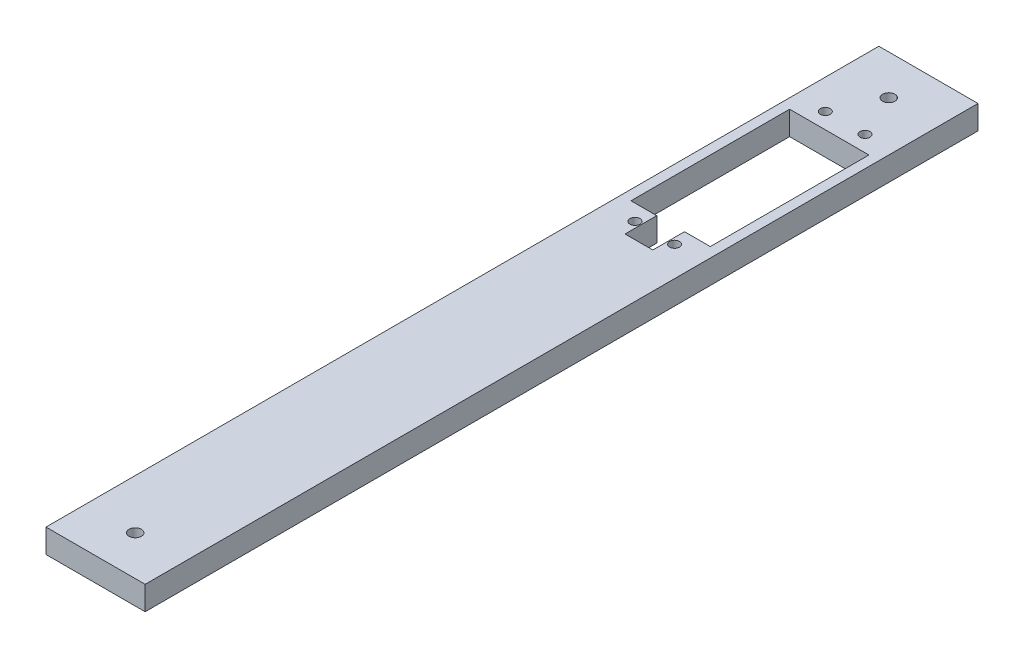
SolidWorks part; units mm, degrees
ref_plane "Спереди" through (0, 0, 0) normal (0, 0, 1) x (1, 0, 0)
ref_plane "Сверху" through (0, 0, 0) normal (0, 1, 0) x (1, 0, 0)
ref_plane "Справа" through (0, 0, 0) normal (1, 0, 0) x (0, 0, -1)
sketch "Эскиз1" plane through (0, 0, 0) normal (0, 1, 0) x (1, 0, 0)
  line L1 (-15.6277, 14.6035) -> (9.3723, 14.6035)
  line L2 (-15.6277, 14.6035) -> (-15.6277, -195.3965)
  line L3 (-15.6277, -195.3965) -> (9.3723, -195.3965)
  line L4 (9.3723, 14.6035) -> (9.3723, -195.3965)
  point P4 (9.3723, -5.921)
  dimension "D1" = 25
  dimension "D2" = 210
extrude "Бобышка-Вытянуть1" add sketch "Эскиз1" along normal blind 6 contours L2 L3 L4 L1
sketch "Эскиз2" plane through (0, 6, 0) normal (0, 1, 0) x (1, 0, 0)
  line L0 (-3.1277, 14.6035) -> (-3.1277, -195.3965) construction
  line L1 (-15.6277, 14.6035) -> (9.3723, 14.6035) construction
  line L2 (-15.6277, -195.3965) -> (9.3723, -195.3965) construction
  line L3 (-15.6277, -90.3965) -> (9.3723, -90.3965) construction
  line L4 (-15.6277, 14.6035) -> (-15.6277, -195.3965) construction
  line L5 (9.3723, 14.6035) -> (9.3723, -195.3965) construction
  circle A1 centre (-3.1277, 4.6035) radius 1.55
  circle A2 centre (-3.1277, -185.3965) radius 1.55
  dimension "D1" = 10
  dimension "D2" = 3.1
extrude "Вырез-Вытянуть1" cut sketch "Эскиз2" against normal blind 6
sketch "Эскиз3" plane through (0, 6, 0) normal (0, 1, 0) x (1, 0, 0)
  line L0 (-3.1277, 14.6035) -> (-3.1277, -195.3965) construction
  line L1 (-13.1277, -10.3965) -> (6.8723, -10.3965)
  line L2 (-13.1277, -10.3965) -> (-13.1277, -50.3965)
  line L3 (-13.1277, -50.3965) -> (-6.6277, -50.3965)
  line L4 (6.8723, -10.3965) -> (6.8723, -50.3965)
  line L5 (-15.6277, 14.6035) -> (9.3723, 14.6035) construction
  line L6 (-15.6277, -195.3965) -> (9.3723, -195.3965) construction
  line L7 (0.3723, -50.3965) -> (6.8723, -50.3965)
  line L8 (-6.6277, -58.3965) -> (0.3723, -58.3965)
  line L9 (-6.6277, -58.3965) -> (-6.6277, -50.3965)
  line L11 (0.3723, -58.3965) -> (0.3723, -50.3965)
  line L12 (-6.6277, -58.3965) -> (0.3723, -50.3965) construction
  line L13 (-6.6277, -50.3965) -> (0.3723, -58.3965) construction
  line L14 (-13.1277, -30.3965) -> (6.8723, -30.3965) construction
  circle A1 centre (-8.1277, -54.3965) radius 1.25
  circle A2 centre (1.8723, -54.3965) radius 1.25
  circle A3 centre (1.8723, -6.3965) radius 1.25
  circle A4 centre (-8.1277, -6.3965) radius 1.25
  point P10 (-3.1277, -10.3965)
  point P11 (-3.1277, -54.3965)
  dimension "D7" = 5
  dimension "D8" = 4
  dimension "D9" = 4
  dimension "D10" = 2.5
  dimension "D1" = 20
  dimension "D2" = 40
  dimension "D3" = 0
  dimension "D4" = 25
  dimension "D5" = 8
  dimension "D6" = 7
extrude "Вырез-Вытянуть2" cut sketch "Эскиз3" against normal blind 6
